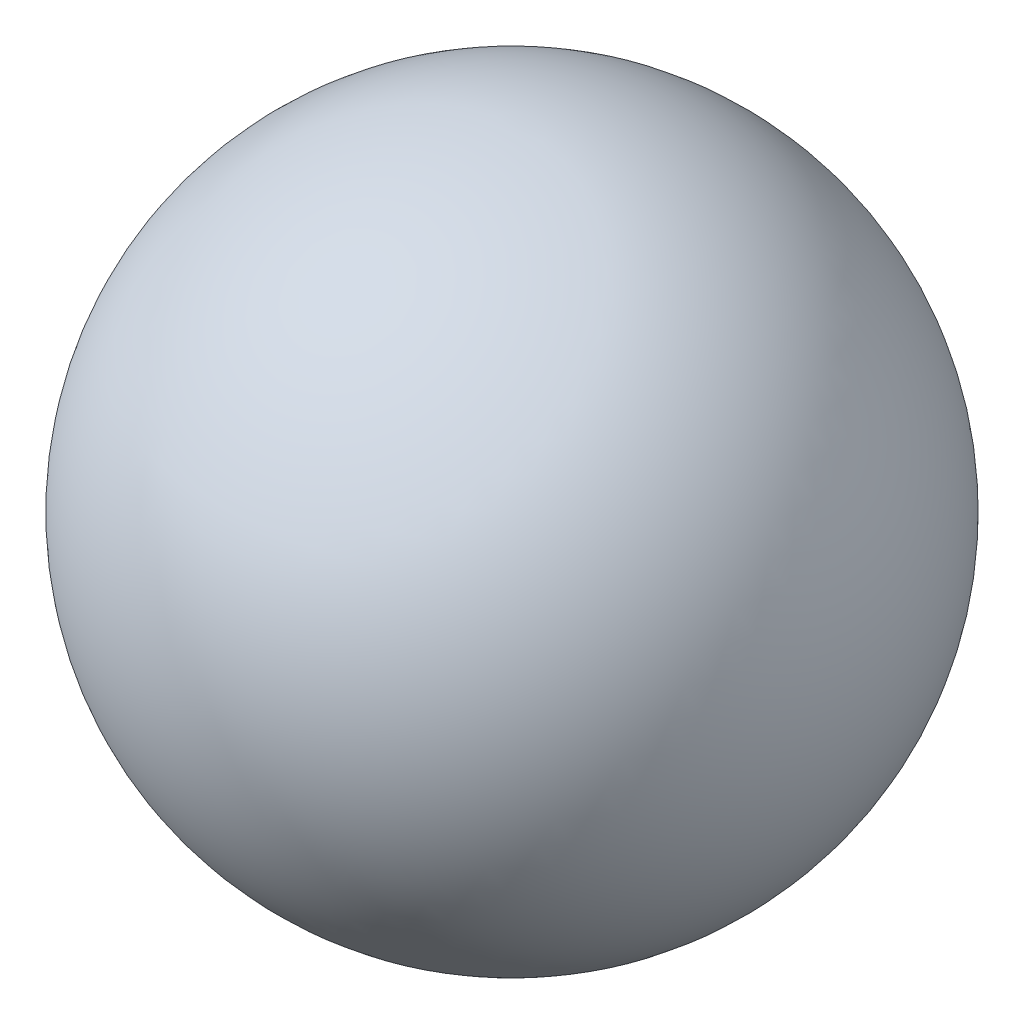
SolidWorks part; units mm, degrees
ref_plane "Front Plane" through (0, 0, 0) normal (0, 0, 1) x (1, 0, 0)
ref_plane "Top Plane" through (0, 0, 0) normal (0, 1, 0) x (1, 0, 0)
ref_plane "Right Plane" through (0, 0, 0) normal (1, 0, 0) x (0, 0, -1)
sketch "Sketch1" plane through (0, 0, 0) normal (0, 0, 1) x (1, 0, 0)
  line L0 (0, -11.6744) -> (0, -10.0642) construction
  line L1 (0, -55) -> (0, 55) construction
  line L2 (0, -20.5309) -> (0, 38.1288) construction
  line L3 (0, 7) -> (0, -7)
  arc A0 (0, 7) -> (0, -7) centre (0, 0) cw
  dimension "D1" = 7
revolve "Revolve1" add sketch "Sketch1" angle 360 about L2
